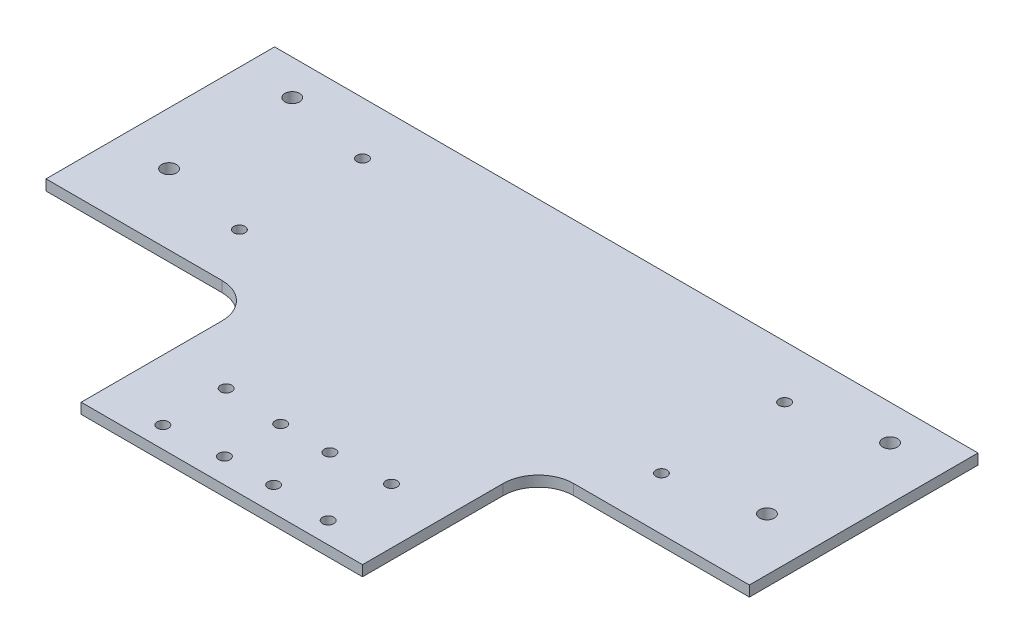
SolidWorks part; units mm, degrees
material "6061-T6 (SS)"
ref_plane "前视基准面" through (0, 0, 0) normal (0, 0, 1) x (1, 0, 0)
ref_plane "上视基准面" through (0, 0, 0) normal (0, 1, 0) x (1, 0, 0)
ref_plane "右视基准面" through (0, 0, 0) normal (1, 0, 0) x (0, 0, -1)
sketch "草图1" plane through (0, 0, 0) normal (0, 1, 0) x (1, 0, 0)
  line L0 (-85, 32.5) -> (-85, -32.5) construction
  line L1 (-100, -32.5) -> (100, -32.5)
  line L2 (-100, -32.5) -> (-100, 32.5)
  line L3 (-100, 32.5) -> (100, 32.5)
  line L4 (100, -32.5) -> (100, 32.5)
  line L5 (-100, -32.5) -> (100, 32.5) construction
  line L6 (-100, 32.5) -> (100, -32.5) construction
  line L7 (0, 32.5) -> (0, -32.5) construction
  line L8 (0, -82.5) -> (0, -32.5) construction
  line L9 (-40, -32.5) -> (40, -32.5)
  line L10 (-40, -32.5) -> (-40, -82.5)
  line L11 (-40, -82.5) -> (40, -82.5)
  line L12 (40, -32.5) -> (40, -82.5)
  circle A0 centre (-85, 22.5) radius 2.1
  circle A1 centre (-85, -12.5) radius 2.1
  circle A2 centre (85, -12.5) radius 2.1
  circle A3 centre (85, 22.5) radius 2.1
  point P0 (0, 0)
  dimension "D4" = 20
  dimension "D5" = 35
  dimension "D1" = 65
  dimension "D2" = 200
  dimension "D3" = 15
  dimension "D6" = 80
  dimension "D7" = 50
extrude "凸台-拉伸1" add sketch "草图1" along normal blind 3 contours L1 L4 L3 L2 A2 A1 A0 A3 | L12 L1 L10 L11
sketch "草图2" plane through (0, 3, 0) normal (0, 1, 0) x (1, 0, 0)
  line L0 (-60, 32.5) -> (-60, -32.5) construction
  line L4 (-100, 0) -> (100, 0) construction
  line L6 (0, 32.5) -> (0, -82.5) construction
  line L7 (-100, 32.5) -> (100, 32.5) construction
  line L8 (-100, -32.5) -> (-100, 32.5) construction
  line L10 (-40, -82.5) -> (40, -82.5) construction
  line L11 (-100, -32.5) -> (-40, -32.5) construction
  circle A0 centre (-60, 17.5) radius 1.6
  circle A1 centre (-60, -17.5) radius 1.6
  circle A2 centre (60, -17.5) radius 1.6
  circle A3 centre (60, 17.5) radius 1.6
  point P6 (0, 0)
  point P13 (0, 0)
  point P26 (0, 0)
  point P27 (0, 0)
  point P28 (0, 0)
  point P29 (0, 0)
  point P30 (0, 0)
  point P31 (0, 0)
  point P32 (0, 0)
  dimension "D2" = 3.2
  dimension "D3" = 15
  dimension "D1" = 40
extrude "避震安装座" cut sketch "草图2" against normal through all from surface at 0 starting at face at (85, 3, 14.6)
sketch "草图3" plane through (0, 3, 0) normal (0, 1, 0) x (1, 0, 0)
  line L0 (0.7261, -25.6829) -> (0.7261, -90.6829) construction
  line L3 (-40, -67.5) -> (40, -67.5) construction
  line L9 (-40, -82.5) -> (40, -82.5) construction
  circle A0 centre (-22.7739, -58.5) radius 1.6
  circle A1 centre (24.2261, -58.5) radius 1.6
  circle A2 centre (24.2261, -76.5) radius 1.6
  circle A3 centre (-22.7739, -76.5) radius 1.6
  circle A4 centre (-6.2739, -59.5) radius 1.6
  circle A5 centre (7.7261, -59.5) radius 1.6
  circle A6 centre (7.7261, -75.5) radius 1.6
  circle A7 centre (-6.2739, -75.5) radius 1.6
  point P5 (0, 0)
  point P8 (0, 0)
  point P24 (0, 0)
  point P25 (0, 0)
  point P27 (0, 0)
  point P28 (0, 0)
  point P29 (0, 0)
  dimension "D1" = 3.2
  dimension "D2" = 47
  dimension "D3" = 18
  dimension "D4" = 14
  dimension "D5" = 16
  dimension "D6" = 15
extrude "铰链孔" cut sketch "草图3" against normal through all
fillet "圆角1" radius 10 2 edges at (40, 1.5, 32.5) (-40, 1.5, 32.5)
